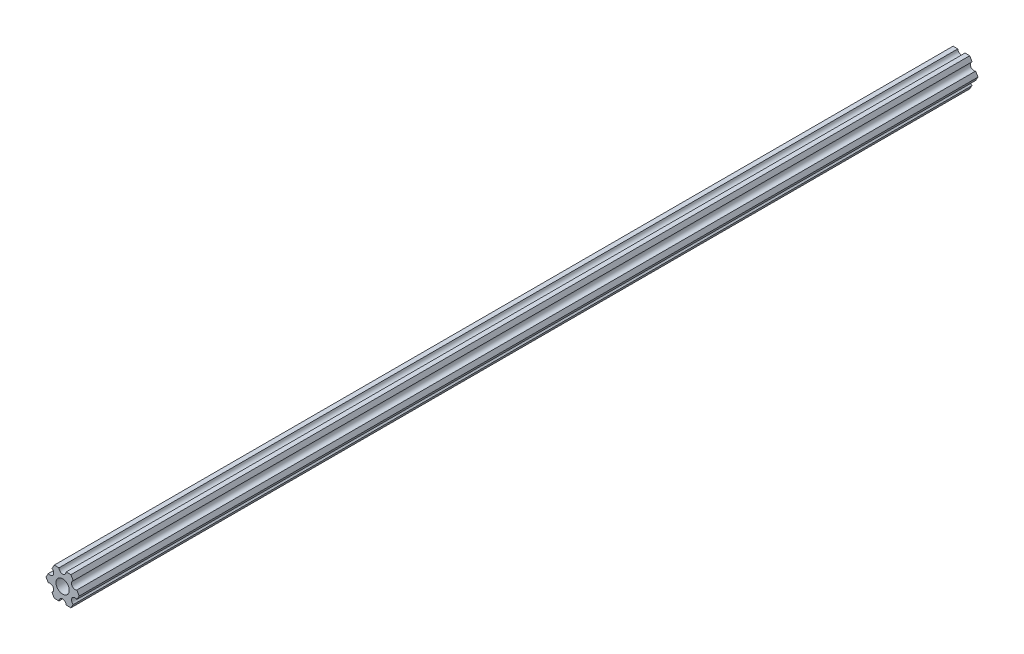
SolidWorks part; units mm, degrees
material "6061 Alloy"
ref_plane "Front Plane" through (0, 0, 0) normal (0, 0, 1) x (1, 0, 0)
ref_plane "Top Plane" through (0, 0, 0) normal (0, 1, 0) x (1, 0, 0)
ref_plane "Right Plane" through (0, 0, 0) normal (1, 0, 0) x (0, 0, -1)
ref_plane "Plane1" through (0, 0, 304.8) normal (0, 0, 1) x (1, 0, 0)
sketch "Sketch1" plane through (0, 0, 304.8) normal (0, 0, 1) x (1, 0, 0)
  line L0 (6.293, -1.8002) -> (7.3323, 0)
  line L1 (7.3323, 0) -> (6.293, 1.8002)
  line L2 (4.7055, 4.5498) -> (3.6662, 6.35)
  line L3 (3.6662, 6.35) -> (1.5875, 6.35)
  line L4 (-1.5875, 6.35) -> (-3.6662, 6.35)
  line L5 (-3.6662, 6.35) -> (-4.7055, 4.5498)
  line L6 (-6.293, 1.8002) -> (-7.3323, 0)
  line L7 (-7.3323, 0) -> (-6.293, -1.8002)
  line L8 (-4.7055, -4.5498) -> (-3.6662, -6.35)
  line L9 (-3.6662, -6.35) -> (-1.5875, -6.35)
  line L10 (1.5875, -6.35) -> (3.6662, -6.35)
  line L11 (3.6662, -6.35) -> (4.7055, -4.5498)
  arc A0 (6.293, 1.8002) -> (4.7055, 4.5498) centre (5.4993, 3.175) cw
  arc A1 (1.5875, 6.35) -> (-1.5875, 6.35) centre (0, 6.35) cw
  arc A2 (-4.7055, 4.5498) -> (-6.293, 1.8002) centre (-5.4993, 3.175) cw
  arc A3 (-6.293, -1.8002) -> (-4.7055, -4.5498) centre (-5.4993, -3.175) cw
  arc A4 (-1.5875, -6.35) -> (1.5875, -6.35) centre (0, -6.35) cw
  arc A5 (4.7055, -4.5498) -> (6.293, -1.8002) centre (5.4993, -3.175) cw
  circle A6 centre (0, 0) radius 2.9337
extrude "Boss-Extrude1" add sketch "Sketch1" against normal blind 396.875
